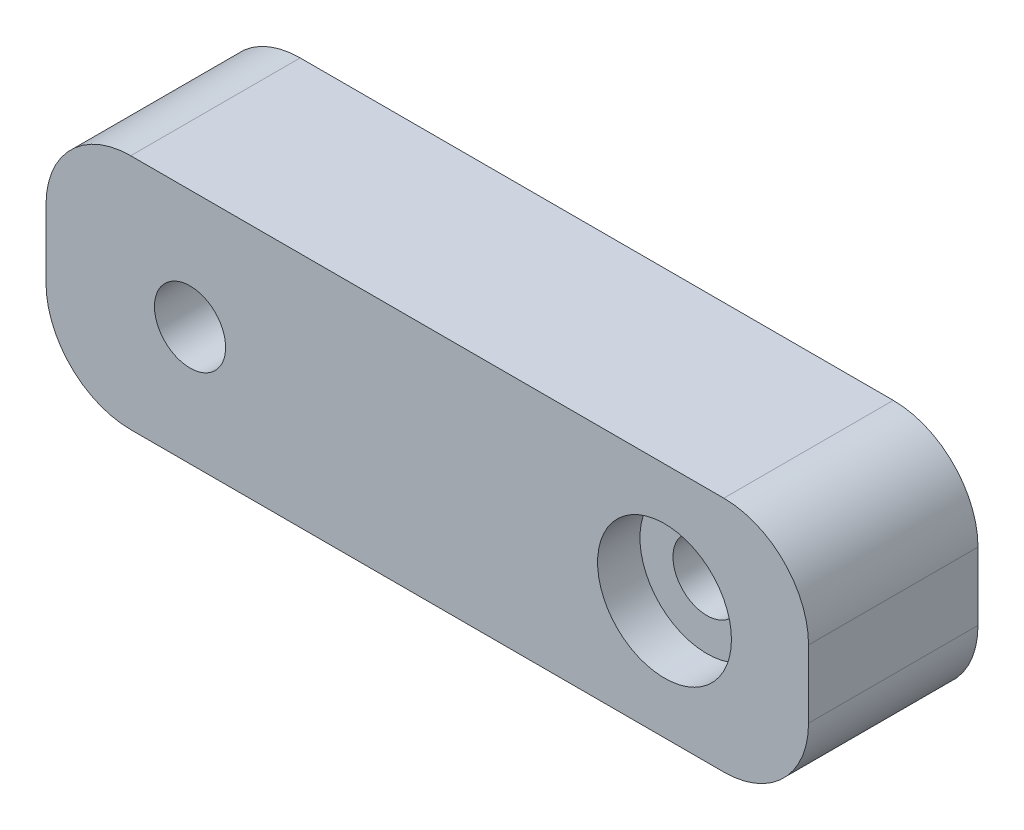
SolidWorks part; units mm, degrees
ref_plane "Front Plane" through (0, 0, 0) normal (0, 0, 1) x (1, 0, 0)
ref_plane "Top Plane" through (0, 0, 0) normal (0, 1, 0) x (1, 0, 0)
ref_plane "Right Plane" through (0, 0, 0) normal (1, 0, 0) x (0, 0, -1)
sketch "Sketch1" plane through (0, 0, 0) normal (0, 0, 1) x (1, 0, 0)
  line L1 (-59.3506, 20.3019) -> (-14.3506, 20.3019)
  line L2 (-59.3506, 20.3019) -> (-59.3506, 6.3019)
  line L3 (-59.3506, 6.3019) -> (-14.3506, 6.3019)
  line L4 (-14.3506, 20.3019) -> (-14.3506, 6.3019)
extrude "Boss-Extrude1" add sketch "Sketch1" along normal blind 10 contours L1 L4 L3 L2
fillet "Fillet1" radius 5 1 edges at (-59.3506, 20.3019, 5)
fillet "Fillet2" radius 5 3 edges at (-14.3506, 6.3019, 5) (-14.3506, 20.3019, 5) (-59.3506, 6.3019, 5)
sketch "Sketch2" plane through (0, 0, 0) normal (0, 0, -1) x (-1, 0, 0)
  line L0 (59.3506, 15.3019) -> (59.3506, 11.3019) construction
  line L1 (54.3506, 20.3019) -> (19.3506, 20.3019) construction
  circle A0 centre (50.8506, 13.3019) radius 4
  point P4 (59.3506, 13.3019)
  dimension "D1" = 8.5
  dimension "D2" = 7
extrude "Cut-Extrude2" cut sketch "Sketch2" against normal blind 2.5 contours A0
sketch "Sketch3" plane through (0, 0, 2.5) normal (0, 0, -1) x (-1, 0, 0)
  circle A2 centre (50.8506, 13.3019) radius 2.1
extrude "Cut-Extrude3" cut sketch "Sketch3" against normal blind 2 contours A2
sketch "Sketch4" plane through (0, 0, 10) normal (0, 0, 1) x (1, 0, 0)
  line L0 (-14.3506, 15.3019) -> (-14.3506, 11.3019) construction
  line L1 (-54.3506, 20.3019) -> (-19.3506, 20.3019) construction
  circle A0 centre (-22.8506, 13.3019) radius 3.95
  dimension "D1" = 8.5
  dimension "D2" = 7
extrude "Cut-Extrude4" cut sketch "Sketch4" against normal blind 5 contours A0
sketch "Sketch5" plane through (0, 0, 5) normal (0, 0, 1) x (1, 0, 0)
  circle A0 centre (-22.8506, 13.3019) radius 2
extrude "Cut-Extrude5" cut sketch "Sketch5" against normal up to next contours A0
sketch "Sketch6" plane through (0, 0, 0) normal (0, 0, -1) x (-1, 0, 0)
  circle A0 centre (22.8506, 13.3019) radius 2.1
  circle A1 centre (22.8506, 13.3019) radius 3.5
sketch "Sketch7" plane through (0, 0, 4.5) normal (0, 0, -1) x (-1, 0, 0)
  circle A0 centre (50.8506, 13.3019) radius 2.1
extrude "Cut-Extrude6" cut sketch "Sketch7" against normal through all
sketch "Sketch9" plane through (0, 0, 5) normal (0, 0, 1) x (1, 0, 0)
  circle A0 centre (-22.8506, 13.3019) radius 2 construction
  circle A1 centre (-22.8506, 13.3019) radius 3.95
  circle A2 centre (-22.8506, 13.3019) radius 3.95
  circle A3 centre (-22.8506, 13.3019) radius 2
  dimension "D1" = 0
extrude "Boss-Extrude2" add sketch "Sketch9" along normal blind 2.5
sketch "Sketch10" plane through (0, 0, 0) normal (0, 0, -1) x (-1, 0, 0)
  line L0 (22.8506, 13.3019) -> (22.8506, 17.3434) construction
  line L1 (22.8506, 13.3019) -> (22.8506, 9.2605) construction
  line L2 (22.8506, 17.3434) -> (20.4153, 15.9374) construction
  line L3 (22.8506, 17.3434) -> (19.3506, 15.3227)
  line L4 (19.3506, 15.3227) -> (19.3506, 11.2812)
  line L5 (19.3506, 11.2812) -> (22.8506, 9.2605)
  line L6 (22.8506, 17.3434) -> (29.3538, 13.5888) construction
  line L7 (22.8506, 17.3434) -> (26.3506, 15.3227)
  line L8 (26.3506, 15.3227) -> (26.3506, 11.2812)
  line L9 (26.3506, 11.2812) -> (22.8506, 9.2605)
  line L10 (19.3506, 13.3019) -> (26.3506, 13.3019) construction
  circle A0 centre (22.8506, 13.3019) radius 2 construction
  circle A1 centre (22.8506, 13.3019) radius 2
  point P14 (22.8506, 13.3019)
  dimension "D1" = 7
  dimension "D4" = 60
extrude "Cut-Extrude7" cut sketch "Sketch10" against normal blind 3
